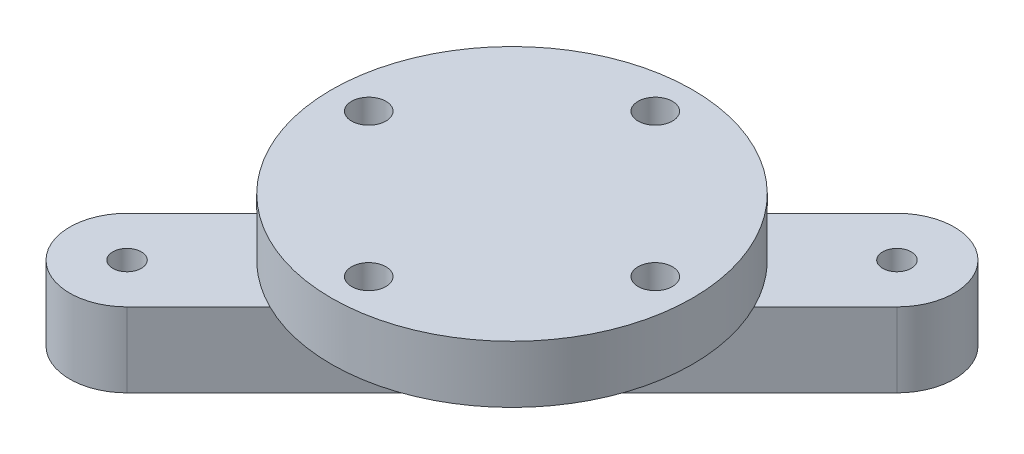
SolidWorks part; units mm, degrees
ref_plane "Front Plane" through (0, 0, 0) normal (0, 0, 1) x (1, 0, 0)
ref_plane "Top Plane" through (0, 0, 0) normal (0, 1, 0) x (1, 0, 0)
ref_plane "Right Plane" through (0, 0, 0) normal (1, 0, 0) x (0, 0, -1)
sketch "Sketch1" plane through (0, 0, 0) normal (0, 1, 0) x (1, 0, 0)
  circle A0 centre (0, 0) radius 31.5
  dimension "D1" = 63
extrude "Boss-Extrude4" add sketch "Sketch1" along normal blind 10
sketch "Sketch3" plane through (0, 0, 0) normal (0, 1, 0) x (1, 0, 0)
  line L0 (0, 0) -> (0, 31.5) construction
  line L1 (0, 31.5) -> (0, -31.5) construction
  line L2 (0, -31.5) -> (0, 0) construction
  line L3 (0, 0) -> (31.5, 0) construction
  line L4 (31.5, 0) -> (-31.5, 0) construction
  circle A0 centre (0, 0) radius 31.5 construction
  circle A1 centre (0, 25) radius 3
  circle A2 centre (25, 0) radius 3
  circle A3 centre (0, -25) radius 3
  circle A4 centre (-25, 0) radius 3
  dimension "D1" = 6
  dimension "D2" = 6
  dimension "D3" = 6
  dimension "D4" = 6
  dimension "D5" = 25
  dimension "D6" = 25
  dimension "D7" = 25
  dimension "D8" = 25
extrude "Cut-Extrude2" cut sketch "Sketch3" along normal blind 10
sketch "Sketch4" plane through (0, 0, 0) normal (0, 1, 0) x (1, 0, 0)
  circle A0 centre (0, 25) radius 5
  circle A1 centre (25, 0) radius 5
  circle A2 centre (0, -25) radius 5
  circle A3 centre (-25, 0) radius 5
  dimension "D1" = 10
  dimension "D2" = 10
  dimension "D3" = 10
  dimension "D4" = 10
extrude "Cut-Extrude3" cut sketch "Sketch4" along normal blind 5
sketch "Sketch5" plane through (0, 0, 0) normal (0, 1, 0) x (1, 0, 0)
  line L0 (-33.5876, -33.5876) -> (33.5876, 33.5876) construction
  line L1 (-40.6586, -26.5165) -> (26.5165, 40.6586)
  line L2 (-26.5165, -40.6586) -> (40.6586, 26.5165)
  arc A0 (-40.6586, -26.5165) -> (-26.5165, -40.6586) centre (-33.5876, -33.5876) ccw
  arc A1 (40.6586, 26.5165) -> (26.5165, 40.6586) centre (33.5876, 33.5876) ccw
  circle A2 centre (-33.5876, -33.5876) radius 2.5
  circle A3 centre (33.5876, 33.5876) radius 2.5
  point P2 (0, 0)
  dimension "D1" = 95
  dimension "D3" = 5
  dimension "D4" = 5
  dimension "D5" = 67.1751
  dimension "D2" = 20
extrude "Boss-Extrude5" add sketch "Sketch5" against normal blind 13
